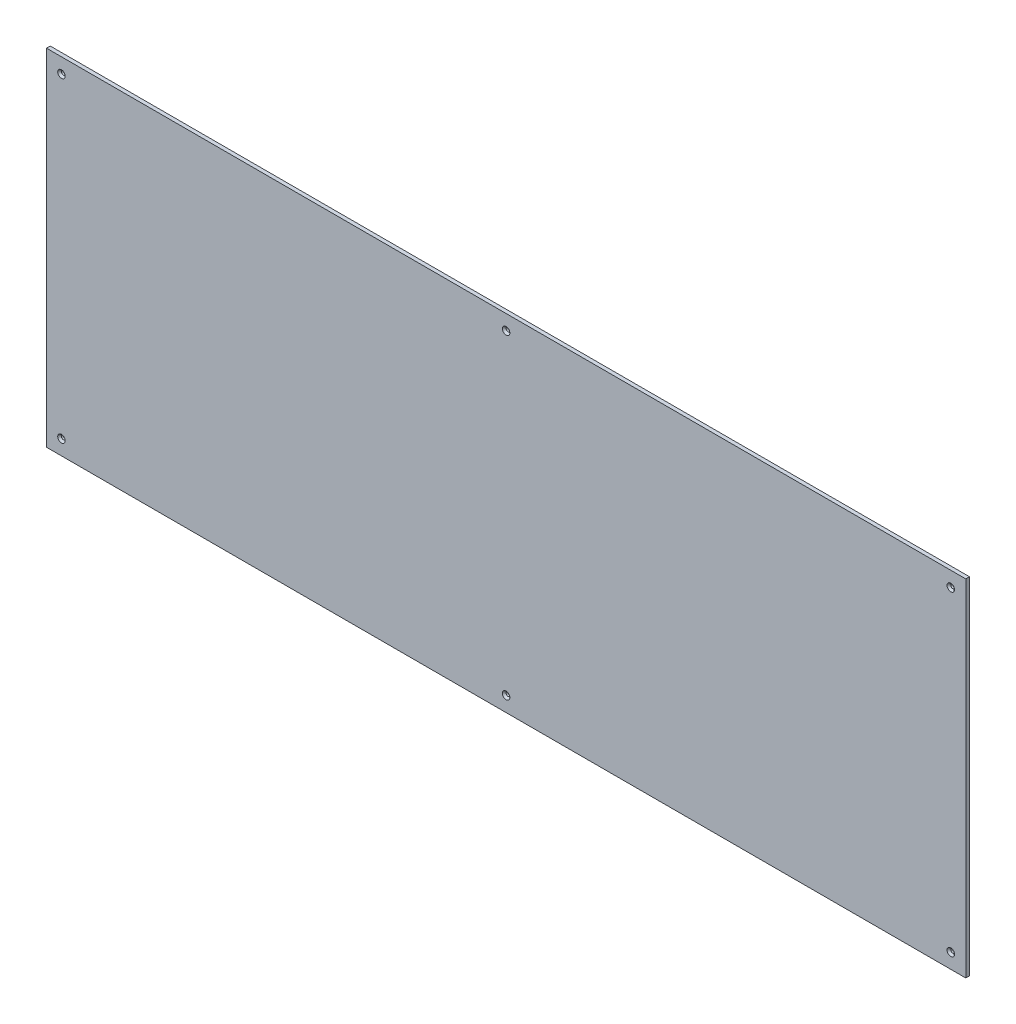
SolidWorks part; units mm, degrees
ref_plane "Plan de face" through (0, 0, 0) normal (0, 0, 1) x (1, 0, 0)
ref_plane "Plan de dessus" through (0, 0, 0) normal (0, 1, 0) x (1, 0, 0)
ref_plane "Plan de droite" through (0, 0, 0) normal (1, 0, 0) x (0, 0, -1)
sketch "Esquisse1" plane through (0, 0, 0) normal (0, 0, 1) x (1, 0, 0)
  line L1 (-55.2092, 33.1404) -> (436.7908, 33.1404)
  line L2 (-55.2092, 33.1404) -> (-55.2092, -151.8596)
  line L3 (-55.2092, -151.8596) -> (436.7908, -151.8596)
  line L4 (436.7908, 33.1404) -> (436.7908, -151.8596)
  dimension "D1" = 492
  dimension "D2" = 185
extrude "Boss.-Extru.1" add sketch "Esquisse1" along normal blind 2
sketch "Esquisse2" plane through (0, 0, 0) normal (0, 0, -1) x (-1, 0, 0)
  line L0 (55.2092, 33.1404) -> (55.2092, -151.8596) construction
  line L1 (-436.7908, 33.1404) -> (55.2092, 33.1404) construction
  line L2 (55.2092, -151.8596) -> (-436.7908, -151.8596) construction
  line L3 (-436.7908, -151.8596) -> (-436.7908, 33.1404) construction
  circle A0 centre (47.2092, 25.1404) radius 1
  circle A1 centre (-190.7908, 25.1404) radius 1
  circle A2 centre (-428.7908, 25.1404) radius 1
  circle A3 centre (47.2092, -143.8596) radius 1
  circle A4 centre (-190.7908, -143.8596) radius 1
  circle A5 centre (-428.7908, -143.8596) radius 1
  dimension "D1" = 8
  dimension "D2" = 8
  dimension "D3" = 8
  dimension "D4" = 8
  dimension "D5" = 8
  dimension "D6" = 8
  dimension "D7" = 8
  dimension "D8" = 8
  dimension "D9" = 8
  dimension "D10" = 8
  dimension "D11" = 246
  dimension "D12" = 246
extrude "Enlèv. mat.-Extru.1" cut sketch "Esquisse2" against normal through all
chamfer "Chanfrein1" distance 1 angle 45 6 edges at (427.7908, -143.8596, 2) (427.7908, 25.1404, 2) (189.7908, 25.1404, 2) (189.7908, -143.8596, 2) (-48.2092, -143.8596, 2) (-48.2092, 25.1404, 2)
